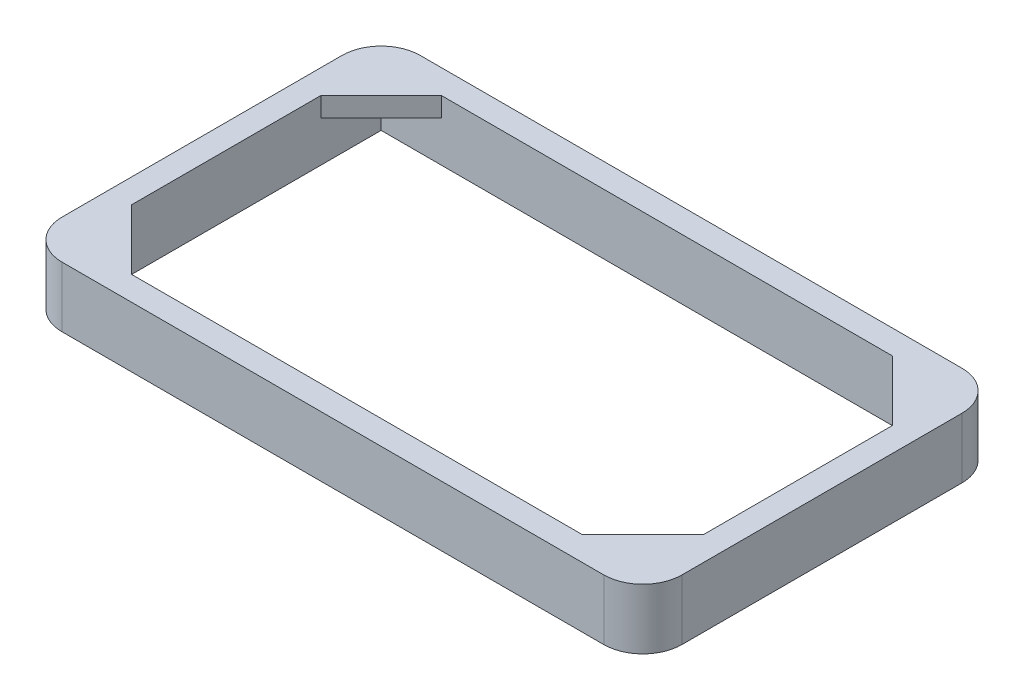
SolidWorks part; units mm, degrees
ref_plane "Front Plane" through (0, 0, 0) normal (0, 0, 1) x (1, 0, 0)
ref_plane "Top Plane" through (0, 0, 0) normal (0, 1, 0) x (1, 0, 0)
ref_plane "Right Plane" through (0, 0, 0) normal (1, 0, 0) x (0, 0, -1)
sketch "Sketch1" plane through (0, 0, 0) normal (0, 1, 0) x (1, 0, 0)
  line L1 (-102.69, 59.325) -> (102.69, 59.325)
  line L2 (-102.69, 59.325) -> (-102.69, -59.325)
  line L3 (-102.69, -59.325) -> (102.69, -59.325)
  line L4 (102.69, 59.325) -> (102.69, -59.325)
  line L5 (-102.69, 59.325) -> (102.69, -59.325) construction
  line L6 (-102.69, -59.325) -> (102.69, 59.325) construction
  line L7 (94.69, 51.325) -> (-94.69, 51.325)
  line L8 (94.69, 51.325) -> (94.69, -51.325)
  line L9 (94.69, -51.325) -> (-94.69, -51.325)
  line L10 (-94.69, 51.325) -> (-94.69, -51.325)
  line L11 (94.69, 51.325) -> (-94.69, -51.325) construction
  line L12 (94.69, -51.325) -> (-94.69, 51.325) construction
  point P0 (0, 0)
  point P6 (0, 0)
  dimension "D1" = 205.38
  dimension "D2" = 118.65
  dimension "D3" = 8
  dimension "D4" = 8
extrude "Boss-Extrude1" add sketch "Sketch1" along normal blind 13.5
sketch "Sketch3" plane through (0, 13.5, 0) normal (0, 1, 0) x (1, 0, 0)
  line L0 (-94.69, 31.325) -> (-74.69, 51.325)
  line L1 (-94.69, 51.325) -> (-94.69, -51.325) construction
  line L2 (94.69, 51.325) -> (-94.69, 51.325) construction
  line L3 (0, 51.325) -> (0, -51.325) construction
  line L4 (-94.69, -51.325) -> (94.69, -51.325) construction
  line L5 (-94.69, 0) -> (94.69, 0) construction
  line L6 (94.69, -51.325) -> (94.69, 51.325) construction
  line L7 (94.69, 31.325) -> (74.69, 51.325)
  line L8 (94.69, -31.325) -> (74.69, -51.325)
  line L9 (-94.69, -31.325) -> (-74.69, -51.325)
  line L10 (-94.69, 31.325) -> (-94.69, -31.325)
  line L11 (-74.69, 51.325) -> (74.69, 51.325)
  line L12 (94.69, 31.325) -> (94.69, -31.325)
  line L13 (-74.69, -51.325) -> (74.69, -51.325)
  line L15 (-102.69, 59.325) -> (102.69, 59.325)
  line L16 (-102.69, 59.325) -> (-102.69, -59.325)
  line L17 (-102.69, -59.325) -> (102.69, -59.325)
  line L18 (102.69, 59.325) -> (102.69, -59.325)
  dimension "D1" = 20
  dimension "D2" = 20
extrude "Boss-Extrude2" add sketch "Sketch3" along normal blind 6.5
sketch "Sketch4" plane through (0, 13.5, 0) normal (0, -1, 0) x (1, 0, 0)
  line L0 (-102.69, -59.325) -> (-102.69, 59.325) construction
  line L1 (-102.69, 59.325) -> (102.69, 59.325) construction
  line L2 (0, 51.325) -> (0, -51.325) construction
  line L3 (-94.69, 51.325) -> (94.69, 51.325) construction
  line L4 (94.69, -51.325) -> (-94.69, -51.325) construction
  line L5 (-94.69, 0) -> (94.69, 0) construction
  line L6 (-94.69, -51.325) -> (-94.69, 51.325) construction
  line L7 (94.69, 51.325) -> (94.69, -51.325) construction
  circle A0 centre (-88.94, 45.575) radius 2.5
  circle A1 centre (88.94, 45.575) radius 2.5
  circle A2 centre (88.94, -45.575) radius 2.5
  circle A3 centre (-88.94, -45.575) radius 2.5
  dimension "D3" = 5
  dimension "D1" = 13.75
  dimension "D2" = 13.75
extrude "Cut-Extrude1" cut sketch "Sketch4" against normal blind 6
fillet "Fillet1" radius 12.94 4 edges at (102.69, 10, 59.325) (102.69, 10, -59.325) (-102.69, 10, 59.325) (-102.69, 10, -59.325)
